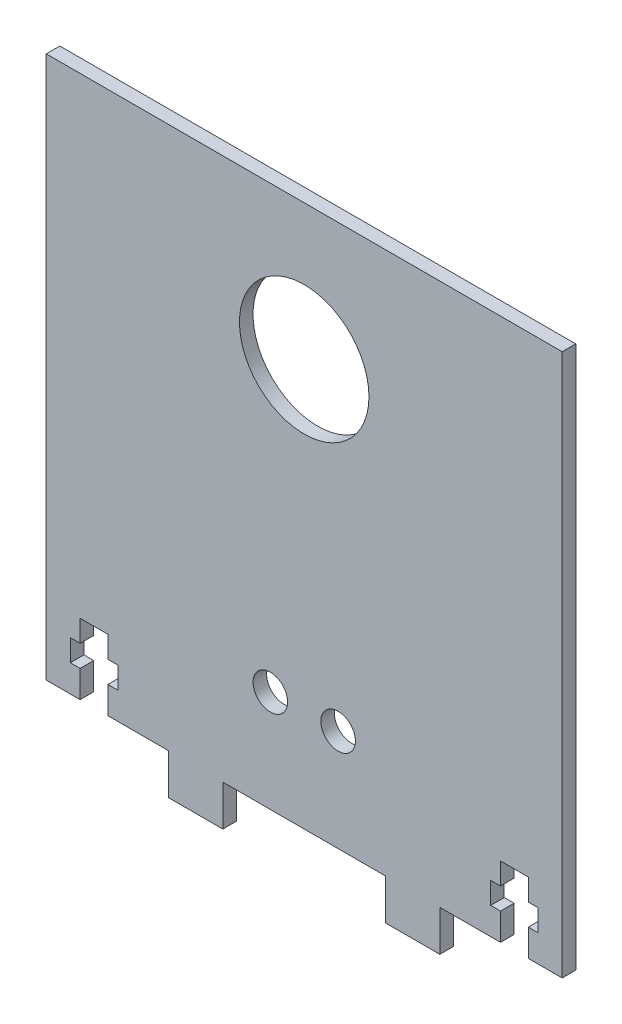
SolidWorks part; units mm, degrees
ref_plane "前视基准面" through (0, 0, 0) normal (0, 0, 1) x (1, 0, 0)
ref_plane "上视基准面" through (0, 0, 0) normal (0, 1, 0) x (1, 0, 0)
ref_plane "右视基准面" through (0, 0, 0) normal (1, 0, 0) x (0, 0, -1)
sketch "草图1" plane through (0, 0, 0) normal (0, 0, 1) x (1, 0, 0)
  line L0 (-30.7912, 3.1303) -> (31.2088, 3.1303) construction
  line L1 (-30.7912, 3.1303) -> (-30.7912, 5.1553) construction
  line L2 (-28.7412, 3.1303) -> (-28.7412, 7.1303)
  line L3 (-28.7412, 7.1303) -> (-27.2912, 7.1303)
  line L4 (-27.2912, 7.1303) -> (-27.2912, 10.3303)
  line L5 (-27.2912, 10.3303) -> (-28.7412, 10.3303)
  line L6 (-28.7412, 10.3303) -> (-28.7412, 13.5303)
  line L7 (-28.7412, 13.5303) -> (-32.8412, 13.5303)
  line L8 (-34.2912, 7.1303) -> (-34.2912, 10.3303)
  line L9 (-32.8412, 10.3303) -> (-32.8412, 13.5303)
  line L10 (-32.8412, 3.1303) -> (-32.8412, 7.1303)
  line L11 (-32.8412, 7.1303) -> (-34.2912, 7.1303)
  line L12 (-34.2912, 10.3303) -> (-32.8412, 10.3303)
  line L13 (-32.8412, 3.1303) -> (-37.8412, 3.1303)
  line L14 (-37.8412, 3.1303) -> (-37.8412, 83.1303)
  line L15 (-19.7912, 3.1303) -> (-19.7912, -2.8697)
  line L16 (-19.7912, -2.8697) -> (-11.7912, -2.8697)
  line L17 (-11.7912, -2.8697) -> (-11.7912, 3.1303)
  line L18 (-15.7912, -2.8697) -> (-15.7912, 3.1303) construction
  line L19 (-28.7412, 3.1303) -> (-19.7912, 3.1303)
  line L20 (0.2088, 3.1303) -> (0.2088, -7.8241) construction
  line L21 (-11.7912, 3.1303) -> (12.2088, 3.1303)
  line L22 (16.2088, -2.8697) -> (16.2088, 3.1303) construction
  line L23 (31.2088, 3.1303) -> (31.2088, 5.1553) construction
  line L24 (29.1588, 3.1303) -> (20.2088, 3.1303)
  line L25 (12.2088, -2.8697) -> (12.2088, 3.1303)
  line L26 (20.2088, -2.8697) -> (12.2088, -2.8697)
  line L27 (20.2088, 3.1303) -> (20.2088, -2.8697)
  line L28 (38.2588, 3.1303) -> (38.2588, 83.1303)
  line L29 (33.2588, 3.1303) -> (38.2588, 3.1303)
  line L30 (34.7088, 10.3303) -> (33.2588, 10.3303)
  line L31 (33.2588, 7.1303) -> (34.7088, 7.1303)
  line L32 (33.2588, 3.1303) -> (33.2588, 7.1303)
  line L33 (33.2588, 10.3303) -> (33.2588, 13.5303)
  line L34 (34.7088, 7.1303) -> (34.7088, 10.3303)
  line L35 (29.1588, 13.5303) -> (33.2588, 13.5303)
  line L36 (29.1588, 10.3303) -> (29.1588, 13.5303)
  line L37 (27.7088, 10.3303) -> (29.1588, 10.3303)
  line L38 (27.7088, 7.1303) -> (27.7088, 10.3303)
  line L39 (29.1588, 7.1303) -> (27.7088, 7.1303)
  line L40 (29.1588, 3.1303) -> (29.1588, 7.1303)
  line L41 (-37.8412, 83.1303) -> (38.2588, 83.1303)
  line L42 (0.2088, 3.1303) -> (0.2088, 63.1303) construction
  circle A0 centre (0.2088, 63.1303) radius 9.55
  circle A1 centre (0.2088, 63.1303) radius 40 construction
  circle A2 centre (-4.7912, 18.1303) radius 2.55
  circle A3 centre (5.2088, 18.1303) radius 2.55
  point P16 (-30.7912, 13.5303)
  point P47 (31.2088, 13.5303)
  dimension "D10" = 19.1
  dimension "D13" = 80
  dimension "D14" = 5.1
  dimension "D1" = 62
  dimension "D2" = 2.05
  dimension "D3" = 3.2
  dimension "D4" = 4
  dimension "D5" = 3.5
  dimension "D6" = 8
  dimension "D7" = 6
  dimension "D8" = 15
  dimension "D9" = 5
  dimension "D11" = 60
  dimension "D12" = 20
  dimension "D15" = 45
  dimension "D16" = 5
extrude "凸台-拉伸1" add sketch "草图1" along normal blind 2
sketch "草图2" plane through (0, 3.1303, 0) normal (0, -1, 0) x (1, 0, 0)
  line L0 (29.1588, 1) -> (33.2588, 1) construction
  line L1 (29.1588, 2) -> (29.1588, 0) construction
  line L2 (33.2588, 2) -> (33.2588, 0) construction
  circle A0 centre (31.2088, 1) radius 2.05
